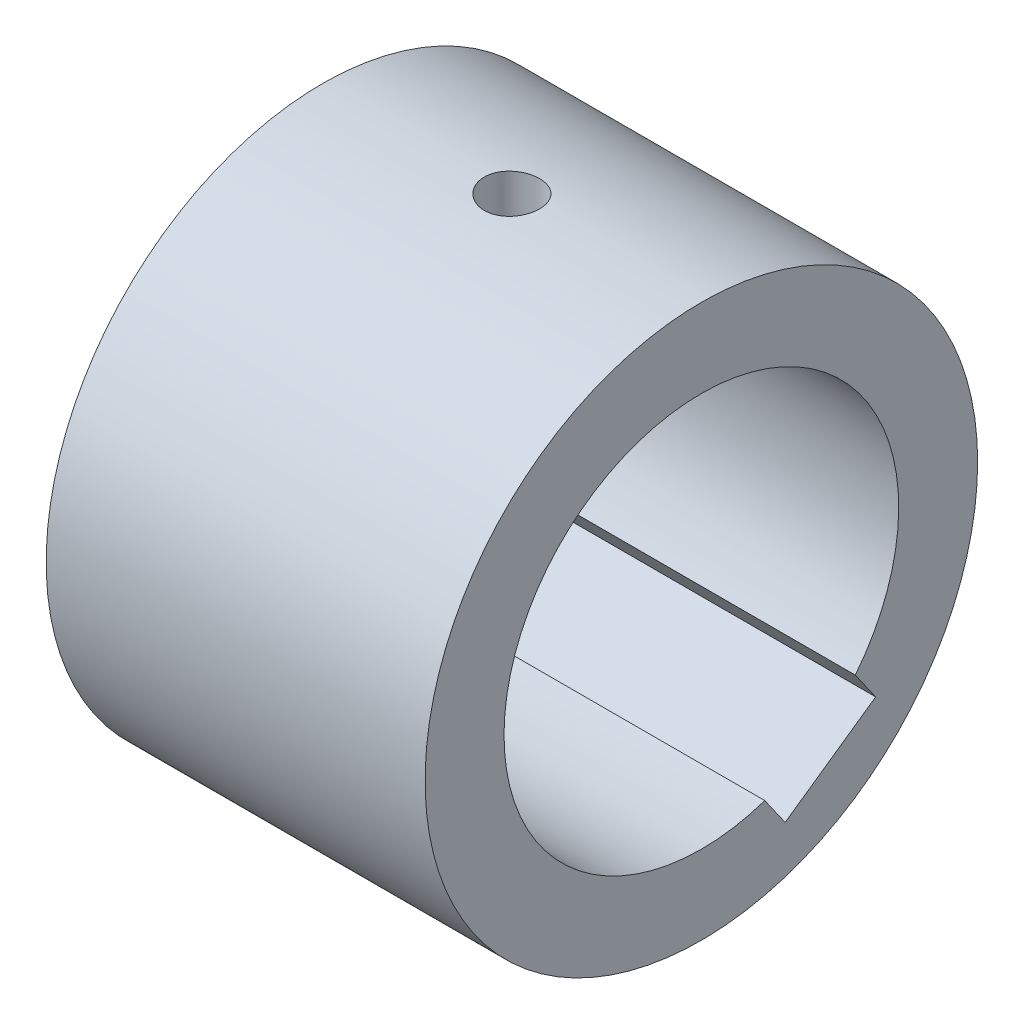
SolidWorks part; units mm, degrees
material "ASTM A36"
ref_plane "Front Plane" through (0, 0, 0) normal (0, 0, 1) x (1, 0, 0)
ref_plane "Top Plane" through (0, 0, 0) normal (0, 1, 0) x (1, 0, 0)
ref_plane "Right Plane" through (0, 0, 0) normal (1, 0, 0) x (0, 0, -1)
sketch "Sketch1" plane through (0, 0, 0) normal (1, 0, 0) x (0, 0, -1)
  circle A0 centre (0, 0) radius 25
  circle A1 centre (0, 0) radius 35
  dimension "D1" = 50
  dimension "D2" = 70
extrude "Boss-Extrude1" add sketch "Sketch1" along normal mid plane 48
sketch "Sketch5" plane through (24, 0, 0) normal (1, 0, 0) x (0, 0, -1)
  line L0 (0, 0) -> (17.3893, -24.8345) construction
  line L1 (22.081, -19.3308) -> (10.6129, -27.3609)
  line L2 (10.6129, -27.3609) -> (2.6183, -15.9435)
  line L3 (2.6183, -15.9435) -> (14.0865, -7.9134)
  line L4 (14.0865, -7.9134) -> (22.081, -19.3308)
  line L5 (0, 0) -> (19.9004, 0) construction
  point P4 (16.3469, -23.3458)
  dimension "D1" = 305
  dimension "D2" = 14
  dimension "D3" = 28.5
extrude "Cut-Extrude2" cut sketch "Sketch5" against normal through all
ref_plane "Plane1" through (0, 35, 0) normal (0, 1, 0) x (-1, 0, 0)
sketch "Sketch6" plane through (0, 35, 0) normal (0, 1, 0) x (-1, 0, 0)
  circle A0 centre (0, 0) radius 3.5
  dimension "D1" = 7
extrude "Cut-Extrude3" cut sketch "Sketch6" against normal blind 24
cosmetic thread "Cosmetic Thread1" parameters "D1"=5, "D2"=8
ref_plane "Plane2" through (11, 0, 0) normal (1, 0, 0) x (0, 0, -1)
